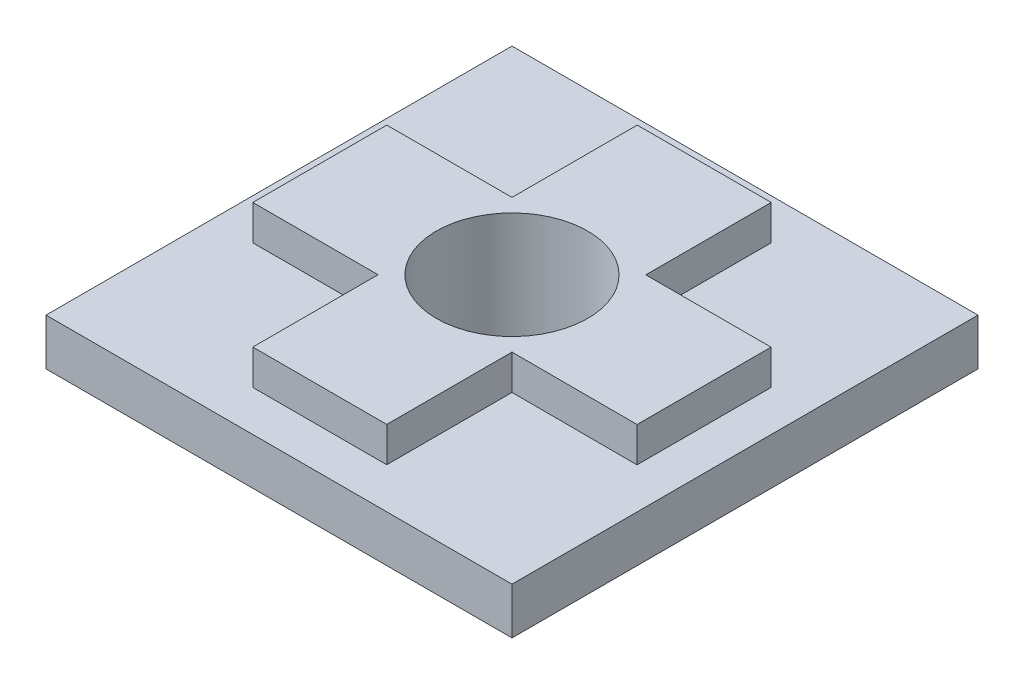
SolidWorks part; units mm, degrees
ref_plane "Front Plane" through (0, 0, 0) normal (0, 0, 1) x (1, 0, 0)
ref_plane "Top Plane" through (0, 0, 0) normal (0, 1, 0) x (1, 0, 0)
ref_plane "Right Plane" through (0, 0, 0) normal (1, 0, 0) x (0, 0, -1)
sketch "Sketch1" plane through (0, 0, 0) normal (0, 1, 0) x (1, 0, 0)
  line L1 (-10, 10) -> (10, 10)
  line L2 (-10, 10) -> (-10, -10)
  line L3 (-10, -10) -> (10, -10)
  line L4 (10, 10) -> (10, -10)
  line L5 (-10, 10) -> (10, -10) construction
  line L6 (-10, -10) -> (10, 10) construction
  point P0 (0, 0)
extrude "Boss-Extrude1" add sketch "Sketch1" along normal blind 2
sketch "Sketch3" plane through (0, 2, 0) normal (0, 1, 0) x (1, 0, 0)
  line L0 (-2.875, 8.25) -> (2.875, 8.25)
  line L1 (0, -55) -> (0, 55) construction
  line L2 (8.25, -2.8825) -> (8.25, 2.8675)
  line L3 (-2.875, 8.25) -> (-2.875, 2.875)
  line L4 (-2.875, -8.25) -> (2.875, -8.25)
  line L5 (-8.25, -2.875) -> (-8.25, 2.875)
  line L6 (-2.875, 2.875) -> (-8.25, 2.875)
  line L7 (-55, 0) -> (55, 0) construction
  line L8 (-8.25, -2.875) -> (-2.875, -2.875)
  line L9 (-2.875, -2.875) -> (-2.875, -8.25)
  line L10 (2.875, -8.25) -> (2.875, -2.875)
  line L11 (2.875, -2.875) -> (8.25, -2.8825)
  line L12 (8.25, 2.8675) -> (2.875, 2.8675)
  line L13 (2.875, 2.8675) -> (2.875, 8.25)
  point P2 (0, 8.25)
  point P8 (8.25, -0.0075)
  point P11 (0, -8.25)
  point P14 (-8.25, 0)
extrude "Boss-Extrude3" add sketch "Sketch3" along normal blind 1.5 and the other way blind 3.5
hole_wizard "Tap Drill for M2.2 Helicoil1" positions "3DSketch1" profile "Sketch5" hole size "M2.2x0.45" standard "ANSI Metric" end condition through all
sketch3d "3DSketch1"
  point P0 (0, 3.5, 0)
  point P3 (0, 0, 0)
sketch "Sketch5" plane through (0, 3.5, 0) normal (1, 0, 0) x (0, 0, 1)
  line L0 (0, 0) -> (0, 5)
  line L1 (0, 5) -> (3.25, 5)
  line L2 (3.25, 5) -> (3.25, 0)
  line L5 (3.25, 0) -> (0, 0)
  line L11 (0, -6.35) -> (0, 107.95) construction
  dimension "Thru Hole Dia." = 6.5
  dimension "Thru Hole Depth" = 5
